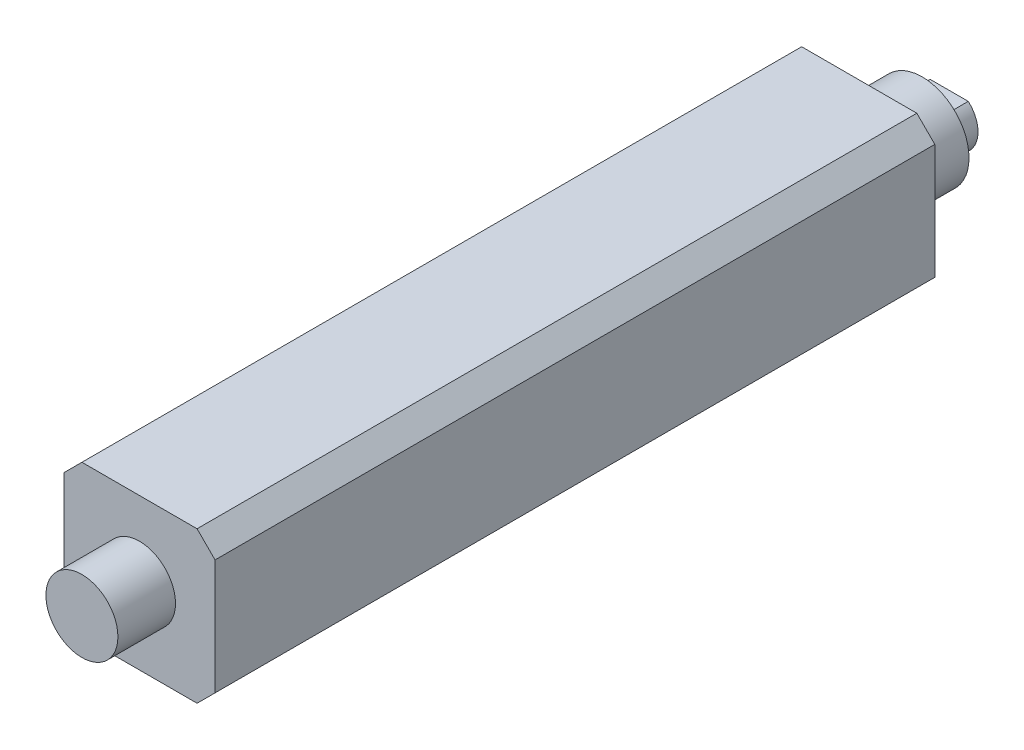
SolidWorks part; units mm, degrees
ref_plane "정면" through (0, 0, 0) normal (0, 0, 1) x (1, 0, 0)
ref_plane "윗면" through (0, 0, 0) normal (0, 1, 0) x (1, 0, 0)
ref_plane "우측면" through (0, 0, 0) normal (1, 0, 0) x (0, 0, -1)
sketch "스케치1" plane through (0, 0, 0) normal (0, 0, 1) x (1, 0, 0)
  line L0 (-21, 16) -> (-16, 21)
  line L1 (-16, -21) -> (16, -21)
  line L2 (-21, -16) -> (-21, 16)
  line L3 (-16, 21) -> (16, 21)
  line L4 (21, -16) -> (21, 16)
  line L5 (-21, -21) -> (21, 21) construction
  line L6 (-21, 21) -> (21, -21) construction
  line L7 (16, 21) -> (21, 16)
  line L8 (-21, -16) -> (-16, -21)
  line L9 (16, -21) -> (21, -16)
  point P0 (0, 0)
  dimension "D1" = 42
  dimension "D2" = 42
extrude "보스-돌출1" add sketch "스케치1" along normal blind 200
sketch "스케치2" plane through (0, 0, 0) normal (0, 0, 1) x (1, 0, 0)
  circle A0 centre (0, 0) radius 15
  dimension "D1" = 30
extrude "보스-돌출2" add sketch "스케치2" against normal blind 3
sketch "스케치3" plane through (0, 0, -3) normal (0, 0, -1) x (-1, 0, 0)
  circle A0 centre (0, 0) radius 13
  dimension "D1" = 26
extrude "보스-돌출3" add sketch "스케치3" along normal blind 14.5
sketch "스케치4" plane through (0, 0, -17.5) normal (0, 0, -1) x (-1, 0, 0)
  circle A0 centre (0, 0) radius 8
  dimension "D1" = 16
extrude "보스-돌출4" add sketch "스케치4" along normal blind 7.5
sketch "스케치5" plane through (0, 0, 200) normal (0, 0, 1) x (1, 0, 0)
  circle A0 centre (0, 0) radius 10
  dimension "D1" = 20
extrude "보스-돌출5" add sketch "스케치5" along normal blind 16
sketch "스케치6" plane through (0, 0, -25) normal (0, 0, -1) x (-1, 0, 0)
  line L0 (-5.2915, 6) -> (5.2915, 6)
  line L1 (-5.2915, -6) -> (5.2915, -6)
  arc A0 (-5.2915, -6) -> (5.2915, -6) centre (0, 0) ccw
  arc A1 (5.2915, 6) -> (-5.2915, 6) centre (0, 0) ccw
  dimension "D1" = 16
  dimension "D2" = 12
extrude "컷-돌출1" cut sketch "스케치6" against normal blind 5
hole_wizard "M10x1.25 탭을 위한 탭 드릴1" positions "스케치8" profile "스케치9" hole size "M10x1.25" standard "ISO"
sketch "스케치8" plane through (0, 0, -25) normal (0, 0, -1) x (-1, 0, 0)
  point P0 (0, 0)
sketch "스케치9" plane through (0, 0, -25) normal (1, 0, 0) x (0, 1, 0)
  line L0 (0, 0) -> (0, 17.6438)
  line L1 (0, 17.6438) -> (4.4, 15)
  line L2 (4.4, 15) -> (4.4, 0)
  line L5 (4.4, 0) -> (0, 0)
  line L10 (0, 17.6438) -> (-4.4, 15) construction
  line L11 (0, -6.35) -> (0, 107.95) construction
  dimension "구멍 지름" = 8.8
  dimension "구멍 깊이" = 15
  dimension "드릴 각도" = 118
